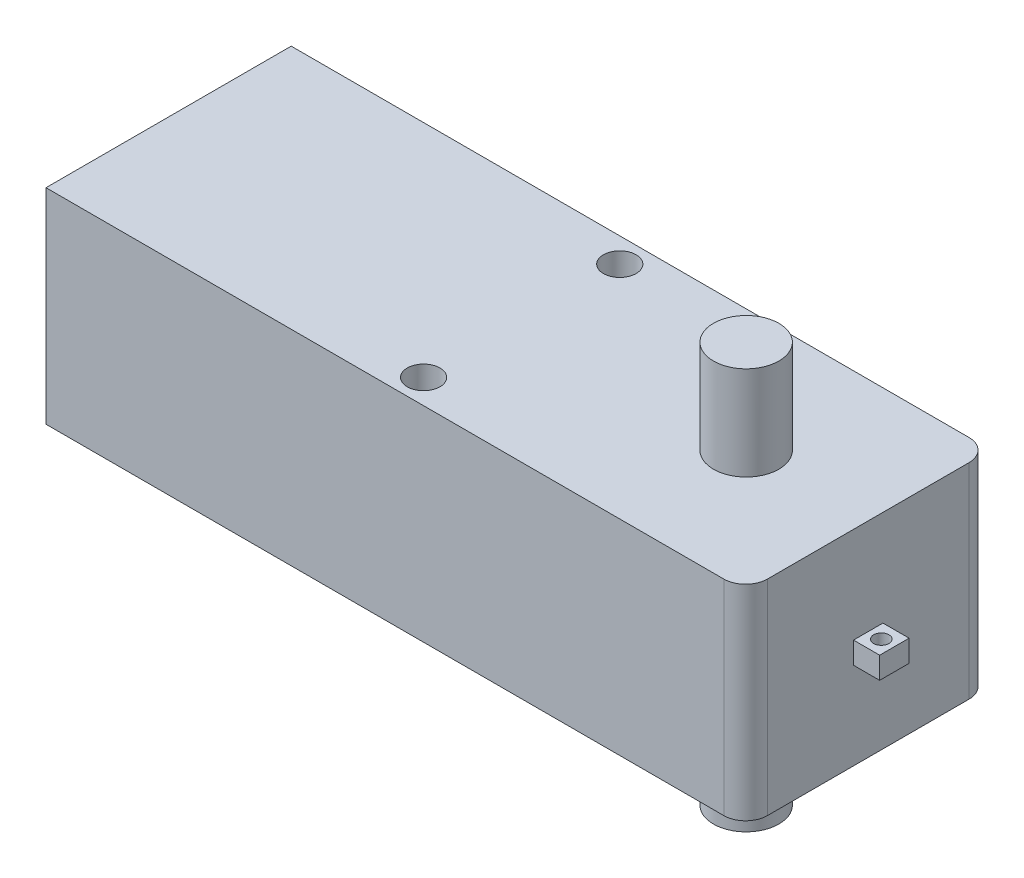
SolidWorks part; units mm, degrees
ref_plane "Front Plane" through (0, 0, 0) normal (0, 0, 1) x (1, 0, 0)
ref_plane "Top Plane" through (0, 0, 0) normal (0, 1, 0) x (1, 0, 0)
ref_plane "Right Plane" through (0, 0, 0) normal (1, 0, 0) x (0, 0, -1)
sketch "Sketch1" plane through (0, 0, 0) normal (0, 1, 0) x (1, 0, 0)
  line L0 (64.2, 11.25) -> (0, 11.25) construction
  line L1 (0, 0) -> (64.2, 0)
  line L2 (0, 0) -> (0, 22.5)
  line L3 (0, 22.5) -> (64.2, 22.5)
  line L4 (64.2, 0) -> (64.2, 22.5)
  circle A1 centre (32.4, 2.25) radius 1.5
  circle A2 centre (32.4, 20.25) radius 1.5
  dimension "D3" = 31.8
  dimension "D4" = 9
  dimension "D5" = 3
  dimension "D1" = 64.2
  dimension "D2" = 22.5
extrude "Boss-Extrude1" add sketch "Sketch1" along normal blind 18.8
ref_plane "Plane1" through (0, 9, 0) normal (0, 1, 0) x (1, 0, 0)
sketch "Sketch2" plane through (0, 9, 0) normal (0, 1, 0) x (1, 0, 0)
  line L0 (64.2, 0) -> (64.2, 22.5) construction
  circle A0 centre (53, 11.25) radius 3
  dimension "D1" = 6
  dimension "D2" = 11.2
extrude "Boss-Extrude2" add sketch "Sketch2" along normal mid plane 36.8
sketch "Sketch3" plane through (0, 9, 0) normal (0, 1, 0) x (1, 0, 0)
  line L0 (64.2, 0) -> (64.2, 22.5) construction
  line L1 (64.2, 9.8993) -> (66.6, 9.8993)
  line L3 (64.2, 12.6007) -> (66.6, 12.6007)
  line L4 (66.6, 9.8993) -> (66.6, 12.6007)
  line L5 (64.2, 11.25) -> (66.6, 12.6007) construction
  line L6 (64.2, 11.25) -> (66.6, 9.8993) construction
  line L7 (64.2, 12.6007) -> (64.2, 9.8993)
  circle A0 centre (65.4, 11.25) radius 0.7
  point P0 (64.2, 11.25)
  dimension "D2" = 1.4
  dimension "D1" = 2.4
  dimension "D3" = 1.2
extrude "Boss-Extrude3" add sketch "Sketch3" along normal mid plane 2
fillet "Fillet1" radius 2 2 edges at (64.2, 9.4, 0) (64.2, 9.4, -22.5)
